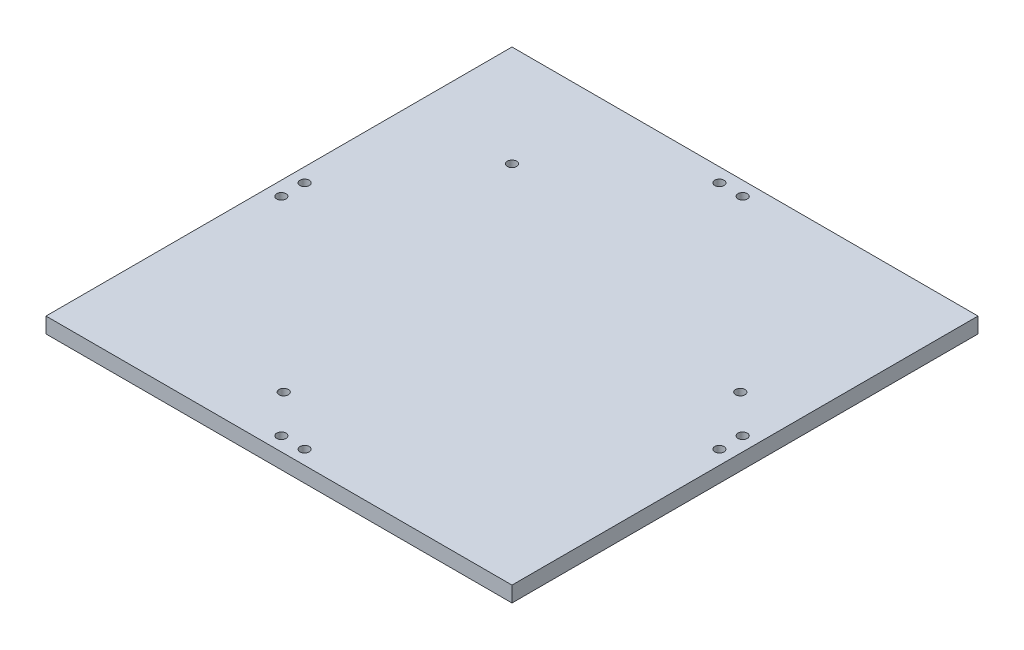
SolidWorks part; units mm, degrees
ref_plane "Front Plane" through (0, 0, 0) normal (0, 0, 1) x (1, 0, 0)
ref_plane "Top Plane" through (0, 0, 0) normal (0, 1, 0) x (1, 0, 0)
ref_plane "Right Plane" through (0, 0, 0) normal (1, 0, 0) x (0, 0, -1)
sketch "Sketch1" plane through (0, 0, 0) normal (0, 1, 0) x (1, 0, 0)
  line L0 (-1000, 0) -> (49000, 0) construction
  line L1 (150, -150) -> (-150, -150)
  line L2 (150, -150) -> (150, 150)
  line L3 (150, 150) -> (-150, 150)
  line L4 (-150, -150) -> (-150, 150)
  line L5 (150, -150) -> (-150, 150) construction
  line L6 (150, 150) -> (-150, -150) construction
  line L7 (0, -1000) -> (0, 49000) construction
  line L8 (-1000, 141) -> (49000, 141) construction
  line L9 (-1000, -141) -> (49000, -141) construction
  line L10 (-141, -973.7022) -> (-141, 49026.2978) construction
  line L11 (141, -1000) -> (141, 49000) construction
  circle A0 centre (0, 0) radius 141 construction
  circle A1 centre (-141, 7.5) radius 3
  circle A2 centre (-141, -7.5) radius 3
  circle A3 centre (7.5, 141) radius 3
  circle A4 centre (-7.5, 141) radius 3
  circle A5 centre (141, -7.5) radius 3
  circle A6 centre (141, 7.5) radius 3
  circle A7 centre (-7.5, -141) radius 3
  circle A8 centre (7.5, -141) radius 3
  point P0 (0, 0)
  point P39 (0, 0)
  dimension "D3" = 282
  dimension "D4" = 6
  dimension "D5" = 6
  dimension "D6" = 7.5
  dimension "D7" = 7.5
  dimension "D1" = 300
  dimension "D2" = 300
  dimension "D8" = 141
  dimension "D9" = 141
  dimension "D10" = 141
  dimension "D11" = 141
  dimension "D12" = 4
extrude "Boss-Extrude1" add sketch "Sketch1" along normal blind 10
sketch "Sketch2" plane through (0, 10, 0) normal (0, 1, 0) x (1, 0, 0)
  line L0 (0, 120) -> (0, 0) construction
  line L2 (-57.9555, -15.5291) -> (-31.0583, -115.9111) construction
  line L4 (-57.9555, -15.5291) -> (-84.8528, 84.8528) construction
  line L5 (15.5291, 57.9555) -> (-84.8528, 84.8528) construction
  line L8 (15.5291, 57.9555) -> (115.9111, 31.0583) construction
  line L9 (42.4264, -42.4264) -> (-31.0583, -115.9111) construction
  line L10 (42.4264, -42.4264) -> (115.9111, 31.0583) construction
  circle A0 centre (0, 0) radius 60 construction
  circle A1 centre (-84.8528, 84.8528) radius 3
  circle A2 centre (115.9111, 31.0583) radius 3
  circle A3 centre (-31.0583, -115.9111) radius 3
  dimension "D1" = 120
  dimension "D2" = 6
  dimension "D3" = 6
  dimension "D4" = 6
extrude "Cut-Extrude1" cut sketch "Sketch2" against normal blind 30
